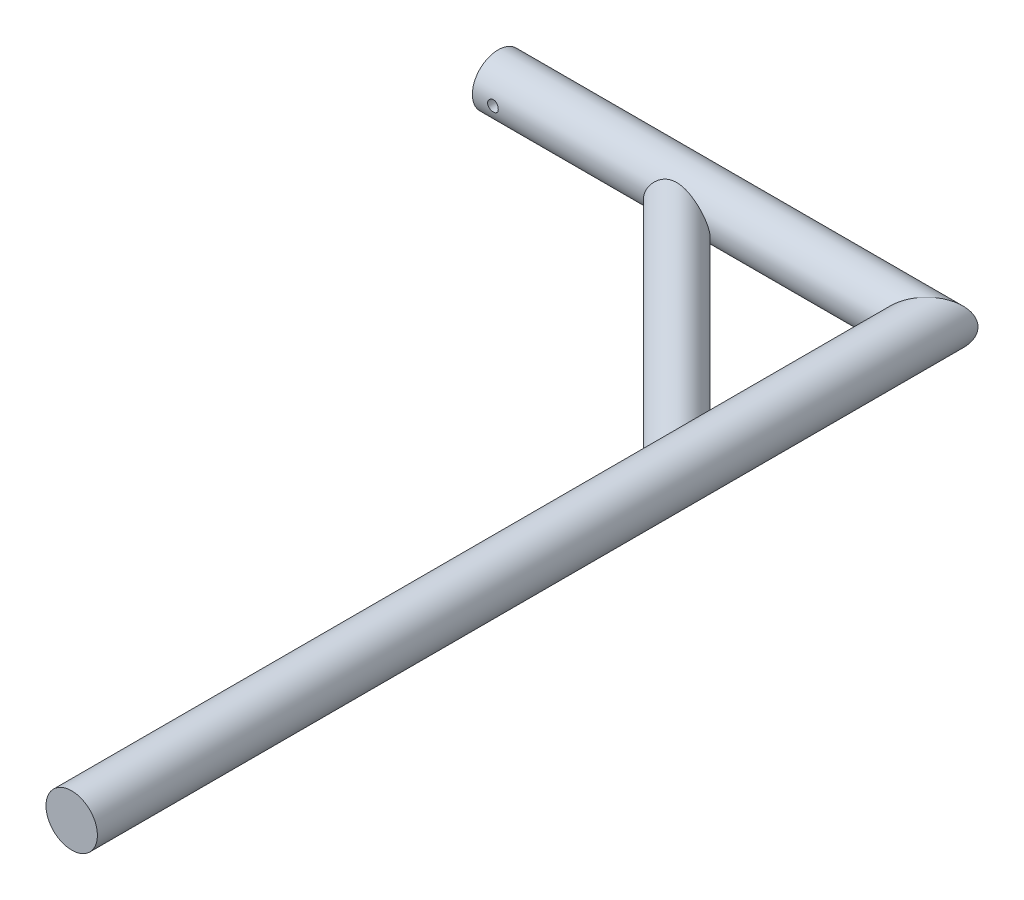
SolidWorks part; units mm, degrees
ref_plane "Front Plane" through (0, 0, 0) normal (0, 0, 1) x (1, 0, 0)
ref_plane "Top Plane" through (0, 0, 0) normal (0, 1, 0) x (1, 0, 0)
ref_plane "Right Plane" through (0, 0, 0) normal (1, 0, 0) x (0, 0, -1)
sketch "Sketch1" plane through (0, 0, 0) normal (0, 1, 0) x (1, 0, 0)
  line L0 (0, 0) -> (0, -798)
  line L1 (0, 0) -> (-400, 0)
  dimension "D1" = 400
sweep "Sweep1" add path "Sketch1" circular profile diameter 48 parameters "D3"=48
ref_plane "Plane1" through (0, 0, 0) normal (0.7071, 0, 0.7071) x (0.7071, 0, -0.7071)
sketch "Sketch10" plane through (0, 0, 0) normal (0.7071, 0, 0.7071) x (0.7071, 0, -0.7071)
  line L0 (0, 0) -> (-329.7805, -9.9248) construction
  circle A0 centre (-164.8903, -4.9624) radius 22
  dimension "D1" = 44
extrude "Extrude-Thin2" add sketch "Sketch10" along normal blind 152 and the other way blind 155 thin thin type one direction reverse wall 2
sketch "Sketch12" plane through (0, 0, 0) normal (0, 0, 1) x (1, 0, 0)
  circle A0 centre (-380.8296, 0) radius 5
  dimension "D1" = 10
extrude "Cut-Extrude1" cut sketch "Sketch12" against normal through all both and the other way through all
